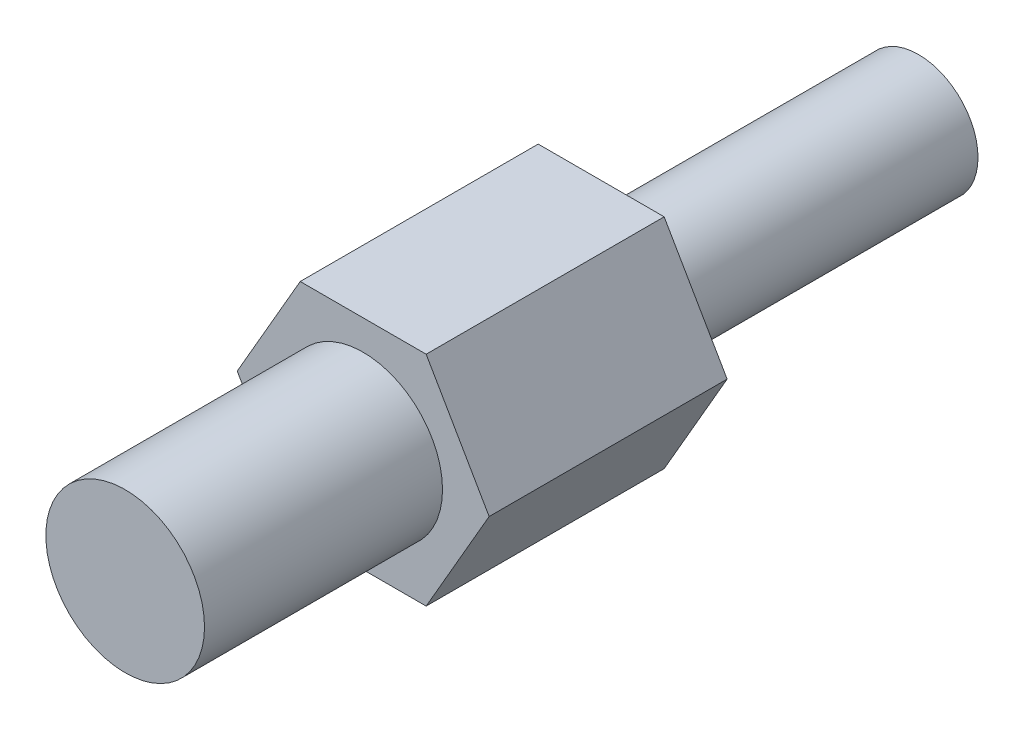
SolidWorks part; units mm, degrees
ref_plane "前视基准面" through (0, 0, 0) normal (0, 0, 1) x (1, 0, 0)
ref_plane "上视基准面" through (0, 0, 0) normal (0, 1, 0) x (1, 0, 0)
ref_plane "右视基准面" through (0, 0, 0) normal (1, 0, 0) x (0, 0, -1)
sketch "草图1" plane through (0, 0, 0) normal (0, 0, 1) x (1, 0, 0)
  line L0 (-28.6627, 0) -> (33.6774, 0) construction
  line L1 (1.5877, -2.75) -> (3.1754, 0)
  line L2 (3.1754, 0) -> (1.5877, 2.75)
  line L3 (1.5877, 2.75) -> (-1.5877, 2.75)
  line L4 (-1.5877, 2.75) -> (-3.1754, 0)
  line L5 (-3.1754, 0) -> (-1.5877, -2.75)
  line L6 (-1.5877, -2.75) -> (1.5877, -2.75)
  circle A0 centre (0, 0) radius 2.75 construction
  dimension "D1" = 5.5
extrude "拉伸1" add sketch "草图1" along normal blind 6
sketch "草图2" plane through (0, 0, 6) normal (0, 0, 1) x (1, 0, 0)
  circle A0 centre (0, 0) radius 2
  dimension "D1" = 4
extrude "拉伸2" add sketch "草图2" along normal blind 6
sketch "草图6" plane through (0, 0, 0) normal (0, 0, -1) x (-1, 0, 0)
  circle A0 centre (0, 0) radius 1.5
  dimension "D1" = 3
extrude "拉伸3" add sketch "草图6" along normal blind 8
